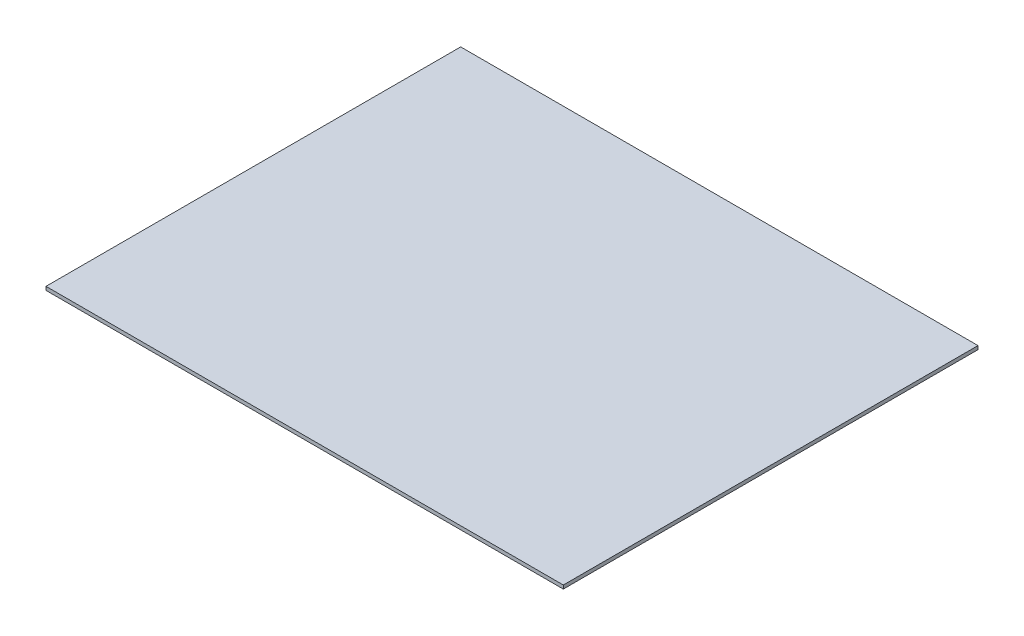
SolidWorks part; units mm, degrees
ref_plane "Front Plane" through (0, 0, 0) normal (0, 0, 1) x (1, 0, 0)
ref_plane "Top Plane" through (0, 0, 0) normal (0, 1, 0) x (1, 0, 0)
ref_plane "Right Plane" through (0, 0, 0) normal (1, 0, 0) x (0, 0, -1)
sketch "Sketch1" plane through (0, 0, 0) normal (0, 1, 0) x (1, 0, 0)
  line L1 (-123.5, 99) -> (123.5, 99)
  line L2 (-123.5, 99) -> (-123.5, -99)
  line L3 (-123.5, -99) -> (123.5, -99)
  line L4 (123.5, 99) -> (123.5, -99)
  line L5 (-123.5, 99) -> (123.5, -99) construction
  line L6 (-123.5, -99) -> (123.5, 99) construction
  point P0 (0, 0)
  dimension "D1" = 198
  dimension "D2" = 247
extrude "Boss-Extrude1" add sketch "Sketch1" along normal blind 1.7
